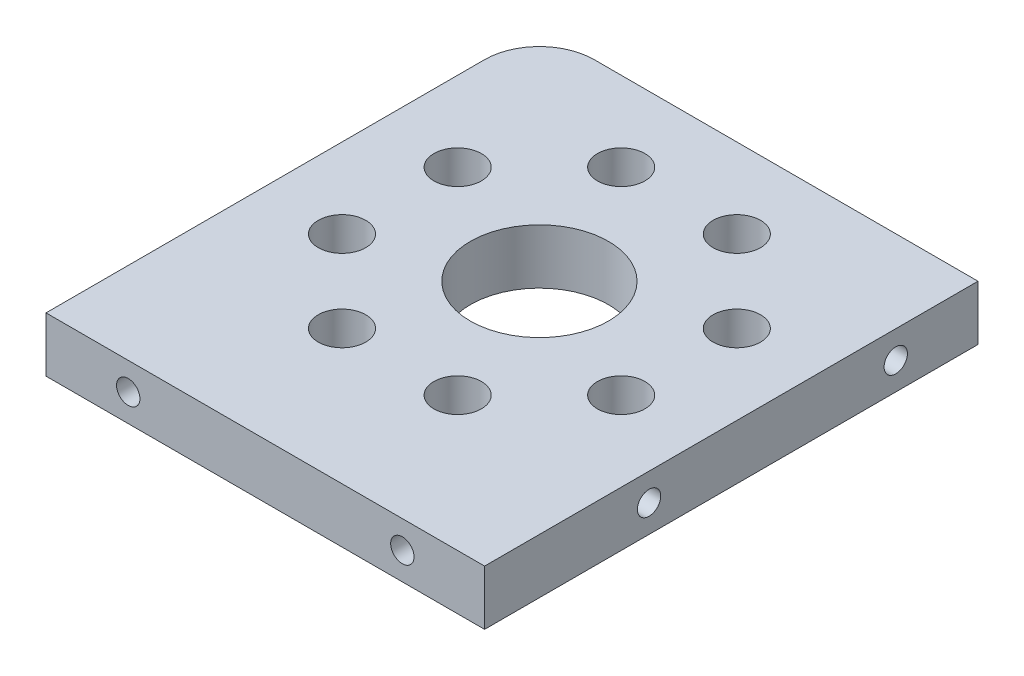
SolidWorks part; units mm, degrees
ref_plane "Front Plane" through (0, 0, 0) normal (0, 0, 1) x (1, 0, 0)
ref_plane "Top Plane" through (0, 0, 0) normal (0, 1, 0) x (1, 0, 0)
ref_plane "Right Plane" through (0, 0, 0) normal (1, 0, 0) x (0, 0, -1)
sketch "Sketch1" plane through (0, 0, 0) normal (0, 1, 0) x (1, 0, 0)
  line L1 (-25.4, 28.575) -> (25.4, 28.575)
  line L2 (-25.4, 28.575) -> (-25.4, -28.575)
  line L3 (-25.4, -28.575) -> (25.4, -28.575)
  line L4 (25.4, 28.575) -> (25.4, -28.575)
  line L5 (-25.4, 28.575) -> (25.4, -28.575) construction
  line L6 (-25.4, -28.575) -> (25.4, 28.575) construction
  point P0 (0, 0)
  dimension "D1" = 50.8
  dimension "D2" = 57.15
extrude "Boss-Extrude1" add sketch "Sketch1" along normal blind 6.35 contours L2 L3 L4 L1
hole_wizard "M5 Clearance Hole1" positions "Sketch2" profile "Sketch3" hole size "M5" standard "ANSI Metric"
sketch "Sketch2" plane through (0, 6.35, 0) normal (0, 1, 0) x (1, 0, 0)
  line L15 (-16.1679, -3.522) -> (-16.1679, 9.872) construction
  line L16 (-16.1679, 9.872) -> (-6.697, 19.3429) construction
  line L17 (-6.697, 19.3429) -> (6.697, 19.3429) construction
  line L18 (6.697, 19.3429) -> (16.1679, 9.872) construction
  line L19 (16.1679, 9.872) -> (16.1679, -3.522) construction
  line L20 (16.1679, -3.522) -> (6.697, -12.9929) construction
  line L21 (6.697, -12.9929) -> (-6.697, -12.9929) construction
  line L22 (-6.697, -12.9929) -> (-16.1679, -3.522) construction
  line L23 (-25.4, 28.575) -> (25.4, 28.575) construction
  circle A0 centre (0, 3.175) radius 17.5 construction
  point P37 (-6.697, -12.9929)
  point P41 (16.1679, -3.522)
  point P67 (-6.697, 19.3429)
  point P69 (6.697, 19.3429)
  point P71 (16.1679, 9.872)
  point P84 (-16.1679, -3.522)
  point P107 (6.697, -12.9929)
  point P110 (-16.1679, 9.872)
  point P113 (213.0164, 15.2168)
  point P114 (-15.5836, 2.5168)
  point P115 (0, 13.8279)
  point P118 (0, 0)
  point P120 (0, 28.575)
  dimension "D1" = 35
  dimension "D2" = 135
  dimension "D3" = 135
  dimension "D4" = 135
  dimension "D5" = 135
  dimension "D6" = 135
  dimension "D7" = 135
  dimension "D8" = 25.4
sketch "Sketch3" plane through (-16.1679, 6.35, -9.872) normal (1, 0, 0) x (0, 0, 1)
  line L0 (0, 0) -> (0, 14.3524)
  line L1 (0, 14.3524) -> (2.75, 12.7)
  line L2 (2.75, 12.7) -> (2.75, 0)
  line L5 (2.75, 0) -> (0, 0)
  line L10 (0, 14.3524) -> (-2.75, 12.7) construction
  line L11 (0, -6.35) -> (0, 107.95) construction
  dimension "Hole Dia." = 5.5
  dimension "Hole Depth" = 12.7
  dimension "Drill Angle" = 118
hole_wizard "Tap Drill for #6-32 Tap1" positions "Sketch4" profile "Sketch5" hole size "#6-32" standard "ANSI Inch"
sketch "Sketch4" plane through (0, 0, 28.575) normal (0, 0, 1) x (1, 0, 0)
  line L0 (-25.4, 6.35) -> (-25.4, 0) construction
  line L1 (25.4, 6.35) -> (25.4, 0) construction
  line L2 (-25.4, 6.35) -> (25.4, 6.35) construction
  point P0 (-15.875, 3.175)
  point P2 (15.875, 3.175)
  point P9 (0, 0)
  dimension "D1" = 9.525
  dimension "D2" = 9.525
  dimension "D3" = 3.175
sketch "Sketch5" plane through (-15.875, 3.175, 28.575) normal (1, 0, 0) x (0, -1, 0)
  line L0 (0, 0) -> (0, 13.5127)
  line L1 (0, 13.5127) -> (1.3525, 12.7)
  line L2 (1.3525, 12.7) -> (1.3525, 0)
  line L5 (1.3525, 0) -> (0, 0)
  line L10 (0, 13.5127) -> (-1.3526, 12.7) construction
  line L11 (0, -6.35) -> (0, 107.95) construction
  dimension "Hole Dia." = 2.7051
  dimension "Hole Depth" = 12.7
  dimension "Drill Angle" = 118
hole_wizard "Tap Drill for #6-32 Tap2" positions "Sketch6" profile "Sketch7" hole size "#6-32" standard "ANSI Inch"
sketch "Sketch6" plane through (25.4, 0, 0) normal (1, 0, 0) x (0, 0, -1)
  line L0 (28.575, 6.35) -> (28.575, 0) construction
  line L2 (-28.575, 6.35) -> (-28.575, 0) construction
  line L3 (28.575, 6.35) -> (-28.575, 6.35) construction
  point P0 (-9.525, 3.175)
  point P2 (19.05, 3.175)
  point P11 (0, 0)
  dimension "D1" = 9.525
  dimension "D2" = 19.05
  dimension "D3" = 3.175
sketch "Sketch7" plane through (25.4, 3.175, 9.525) normal (0, 1, 0) x (0, 0, -1)
  line L0 (0, 0) -> (0, 13.5127)
  line L1 (0, 13.5127) -> (1.3525, 12.7)
  line L2 (1.3525, 12.7) -> (1.3525, 0)
  line L5 (1.3525, 0) -> (0, 0)
  line L10 (0, 13.5127) -> (-1.3525, 12.7) construction
  line L11 (0, -6.35) -> (0, 107.95) construction
  dimension "Hole Dia." = 2.7051
  dimension "Hole Depth" = 12.7
  dimension "Drill Angle" = 118
fillet "Fillet1" radius 6.35 1 edges at (-25.4, 3.175, -28.575)
sketch "Sketch8" plane through (0, 6.35, 0) normal (0, 1, 0) x (1, 0, 0)
  circle A0 centre (0, 3.175) radius 8
  dimension "D1" = 16
extrude "Cut-Extrude1" cut sketch "Sketch8" against normal blind 6.35
